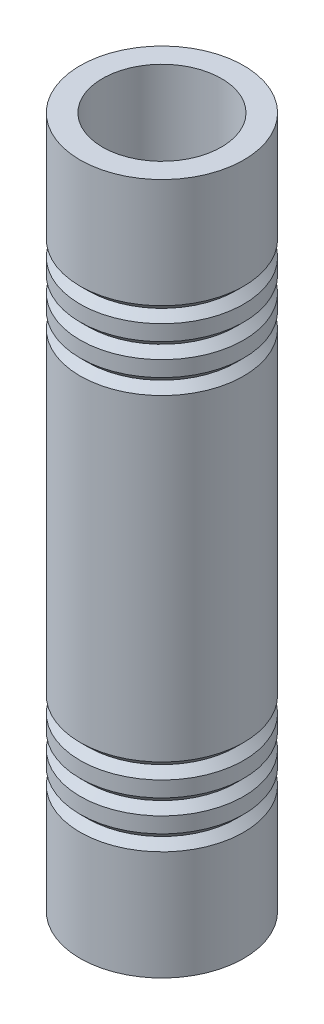
SolidWorks part; units mm, degrees
ref_plane "Front Plane" through (0, 0, 0) normal (0, 0, 1) x (1, 0, 0)
ref_plane "Top Plane" through (0, 0, 0) normal (0, 1, 0) x (1, 0, 0)
ref_plane "Right Plane" through (0, 0, 0) normal (1, 0, 0) x (0, 0, -1)
ref_plane "Plane1" through (0, 0, 0) normal (0, 0, -1) x (-1, 0, 0)
sketch "Sketch1" plane through (0, 0, 0) normal (0, 0, -1) x (-1, 0, 0)
  line L0 (-15.2908, 177.8) -> (-21.0344, 177.8)
  line L1 (-15.2908, 88.9) -> (-21.0344, 88.9) construction
  line L2 (-21.0344, 0) -> (-15.2908, 0)
  line L3 (-15.2908, 0) -> (-15.2908, 177.8)
  line L4 (0, 0) -> (0, 177.8) construction
  line L5 (-21.0344, 137.7) -> (-21.0344, 141.7) construction
  line L6 (-21.0344, 137.7) -> (-21.0344, 133.7)
  line L7 (-21.0344, 133.7) -> (-21.0344, 129.7) construction
  line L8 (-21.0344, 141.7) -> (-21.0344, 145.7)
  line L9 (-21.0344, 145.7) -> (-21.0344, 149.7) construction
  line L10 (-21.0344, 177.8) -> (-21.0344, 149.7)
  line L11 (-21.0344, 129.7) -> (-21.0344, 88.9)
  line L12 (-21.0344, 147.7) -> (-19.0344, 147.7) construction
  line L13 (-21.0344, 139.7) -> (-19.0344, 139.7) construction
  line L14 (-21.0344, 131.7) -> (-19.0344, 131.7) construction
  line L21 (-21.0344, 88.9) -> (-21.0344, 48.1)
  line L22 (-21.0344, 48.1) -> (-21.0344, 44.1) construction
  line L23 (-21.0344, 46.1) -> (-19.0344, 46.1) construction
  line L26 (-21.0344, 44.1) -> (-21.0344, 40.1)
  line L29 (-21.0344, 36.1) -> (-21.0344, 32.1)
  line L32 (-21.0344, 28.1) -> (-21.0344, 0)
  line L33 (-21.0344, 40.1) -> (-21.0344, 36.1) construction
  line L34 (-21.0344, 32.1) -> (-21.0344, 28.1) construction
  line L35 (-21.0344, 30.1) -> (-19.0344, 30.1) construction
  line L36 (-21.0344, 38.1) -> (-19.0344, 38.1) construction
  line L38 (-19.0344, 147.7) -> (-21.0344, 149.7)
  line L39 (-19.0344, 147.7) -> (-21.0344, 145.7)
  line L41 (-19.0344, 139.7) -> (-21.0344, 141.7)
  line L42 (-21.0344, 137.7) -> (-19.0344, 139.7)
  line L44 (-19.0344, 131.7) -> (-21.0344, 133.7)
  line L45 (-19.0344, 131.7) -> (-21.0344, 129.7)
  line L47 (-19.0344, 46.1) -> (-21.0344, 48.1)
  line L48 (-21.0344, 44.1) -> (-19.0344, 46.1)
  line L50 (-19.0344, 38.1) -> (-21.0344, 40.1)
  line L51 (-21.0344, 36.1) -> (-19.0344, 38.1)
  line L53 (-19.0344, 30.1) -> (-21.0344, 32.1)
  line L54 (-21.0344, 28.1) -> (-19.0344, 30.1)
  line L55 (0, 177.8) -> (-15.2908, 177.8) construction
  line L56 (-15.2908, 0) -> (0, 0) construction
  point P8 (-21.0344, 139.7)
  point P12 (-21.0344, 139.7)
  point P34 (0, 0)
  point P36 (-19.0344, 139.7)
  point P40 (-19.0344, 147.7)
  point P43 (-19.0344, 131.7)
  point P46 (-19.0344, 46.1)
  point P49 (-19.0344, 38.1)
  point P52 (-19.0344, 30.1)
  dimension "D1" = 177.8
  dimension "D2" = 5.7436
  dimension "D3" = 50.8
  dimension "D4" = 8
  dimension "D5" = 2
  dimension "D6" = 4
revolve "Revolve1" add sketch "Sketch1" angle 360 about L4
